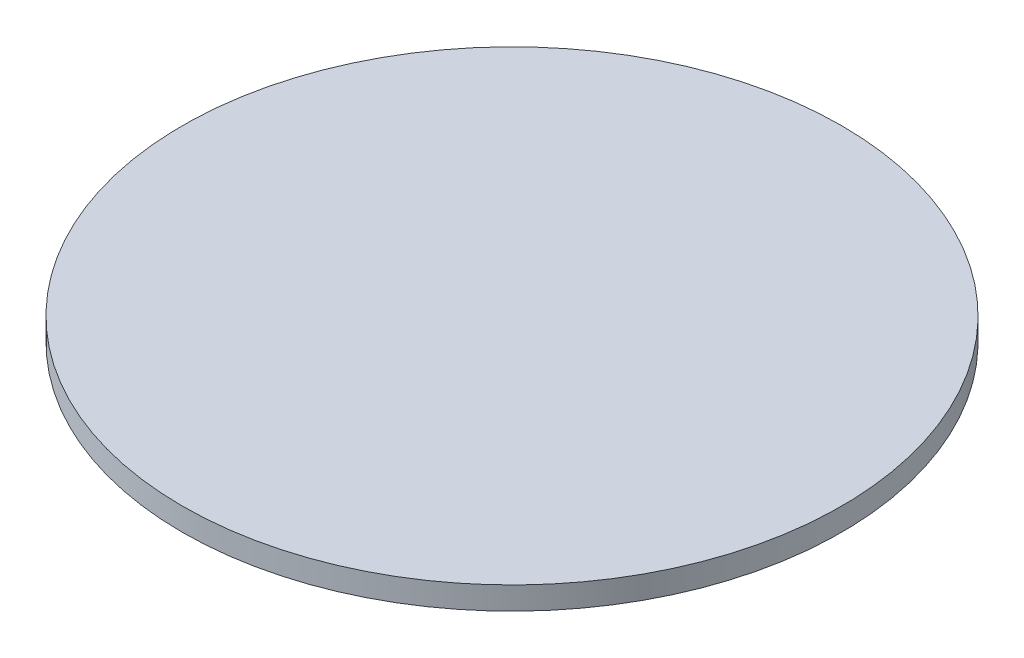
SolidWorks part; units mm, degrees
material "Glass"
ref_plane "Front Plane" through (0, 0, 0) normal (0, 0, 1) x (1, 0, 0)
ref_plane "Top Plane" through (0, 0, 0) normal (0, 1, 0) x (1, 0, 0)
ref_plane "Right Plane" through (0, 0, 0) normal (1, 0, 0) x (0, 0, -1)
sketch "Sketch1" plane through (0, 0, 0) normal (0, 1, 0) x (1, 0, 0)
  circle A0 centre (0, 0) radius 29
  dimension "D1" = 58
extrude "Boss-Extrude1" add sketch "Sketch1" along normal blind 2 contours A0
